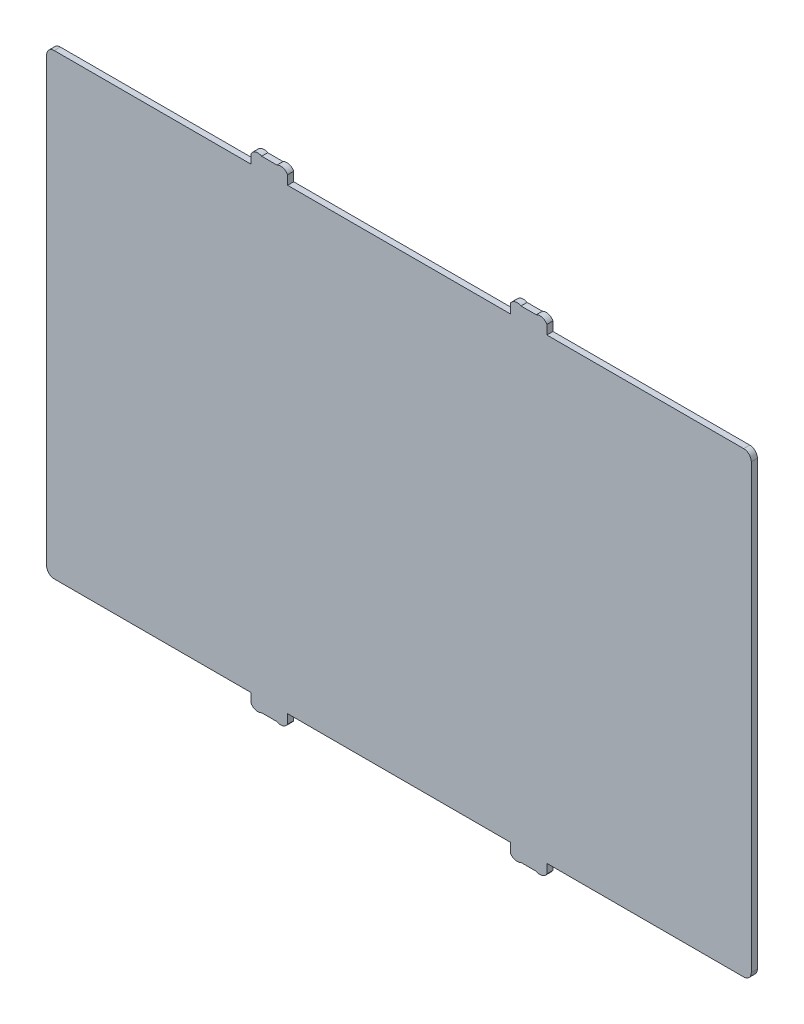
SolidWorks part; units mm, degrees
ref_plane "Спереди" through (0, 0, 0) normal (0, 0, 1) x (1, 0, 0)
ref_plane "Сверху" through (0, 0, 0) normal (0, 1, 0) x (1, 0, 0)
ref_plane "Справа" through (0, 0, 0) normal (1, 0, 0) x (0, 0, -1)
sketch "Эскиз1" plane through (0, 0, 0) normal (0, 0, 1) x (1, 0, 0)
  line L0 (177, -66.2866) -> (323, -66.2866)
  line L1 (323, -366.2866) -> (177, -366.2866)
  line L30 (24, -66.2866) -> (153, -66.2866)
  line L31 (19, -71.2866) -> (19, -361.2866)
  line L32 (24, -366.2866) -> (153, -366.2866)
  line L33 (481, -71.2866) -> (481, -361.2866)
  line L37 (160, -58.2866) -> (170, -58.2866)
  line L39 (160, -374.2866) -> (170, -374.2866)
  line L40 (153, -60.2866) -> (153, -66.2866)
  line L41 (330, -58.2866) -> (340, -58.2866)
  line L42 (177, -60.2866) -> (177, -66.2866)
  line L43 (330, -374.2866) -> (340, -374.2866)
  line L44 (323, -60.2866) -> (323, -66.2866)
  line L45 (347, -60.2866) -> (347, -66.2866)
  line L50 (153, -366.2866) -> (153, -372.2866)
  line L51 (347, -66.2866) -> (476, -66.2866)
  line L53 (177, -366.2866) -> (177, -372.2866)
  line L54 (347, -366.2866) -> (476, -366.2866)
  line L59 (323, -366.2866) -> (323, -372.2866)
  line L60 (347, -366.2866) -> (347, -372.2866)
  arc A0 (24, -66.2866) -> (19, -71.2866) centre (24, -71.2866) ccw
  arc A1 (19, -361.2866) -> (24, -366.2866) centre (24, -361.2866) ccw
  arc A2 (481, -71.2866) -> (476, -66.2866) centre (476, -71.2866) ccw
  arc A3 (481, -361.2866) -> (476, -366.2866) centre (476, -361.2866) cw
  arc A12 (330, -374.2866) -> (323, -372.2866) centre (327.5, -369.7866) cw
  arc A13 (347, -372.2866) -> (340, -374.2866) centre (342.5, -369.7866) cw
  arc A14 (153, -372.2866) -> (160, -374.2866) centre (157.5, -369.7866) ccw
  arc A15 (170, -374.2866) -> (177, -372.2866) centre (172.5, -369.7866) ccw
  arc A16 (153, -60.2866) -> (160, -58.2866) centre (157.5, -62.7866) cw
  arc A17 (177, -60.2866) -> (170, -58.2866) centre (172.5, -62.7866) ccw
  arc A18 (323, -60.2866) -> (330, -58.2866) centre (327.5, -62.7866) cw
  arc A19 (347, -60.2866) -> (340, -58.2866) centre (342.5, -62.7866) ccw
extrude "Бобышка-Вытянуть1" add sketch "Эскиз1" along normal blind 4
